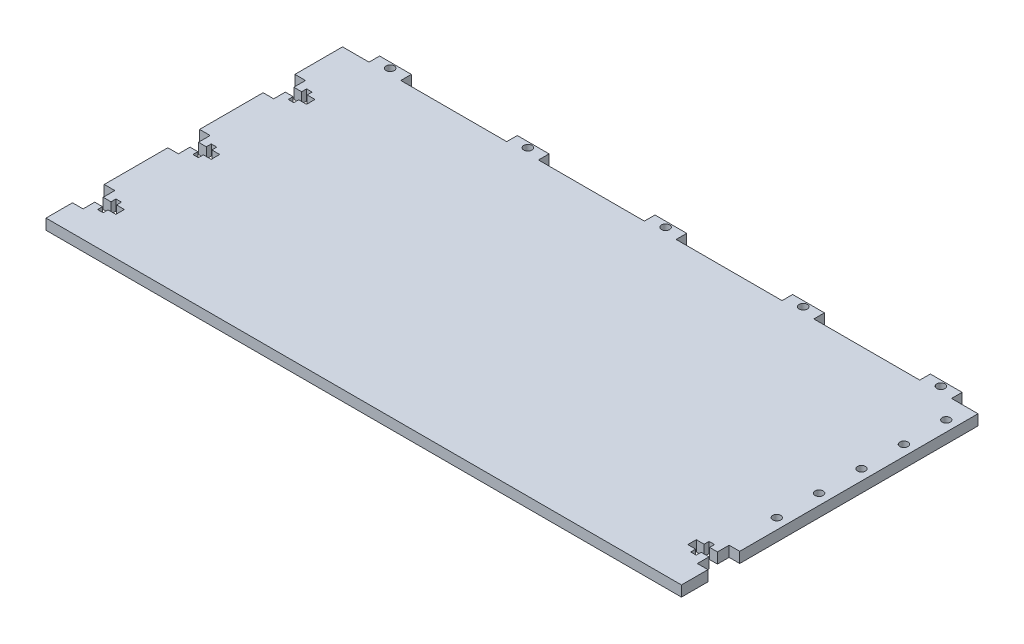
SolidWorks part; units mm, degrees
ref_plane "Front Plane" through (0, 0, 0) normal (0, 0, 1) x (1, 0, 0)
ref_plane "Top Plane" through (0, 0, 0) normal (0, 1, 0) x (1, 0, 0)
ref_plane "Right Plane" through (0, 0, 0) normal (1, 0, 0) x (0, 0, -1)
sketch "Sketch1" plane through (0, 0, 0) normal (0, 1, 0) x (1, 0, 0)
  line L1 (0, 0) -> (381, 0)
  line L2 (0, 0) -> (0, 177.8)
  line L3 (0, 177.8) -> (381, 177.8)
  line L4 (381, 0) -> (381, 177.8)
  dimension "D1" = 381
  dimension "D2" = 177.8
extrude "Boss-Extrude1" add sketch "Sketch1" along normal blind 6.35
sketch "Sketch2" plane through (0, 6.35, 0) normal (0, 1, 0) x (1, 0, 0)
  line L0 (381, 177.8) -> (0, 177.8) construction
  line L1 (15.875, 177.8) -> (34.925, 177.8)
  line L2 (15.875, 177.8) -> (15.875, 184.15)
  line L3 (15.875, 184.15) -> (34.925, 184.15)
  line L4 (34.925, 177.8) -> (34.925, 184.15)
  line L5 (0, 177.8) -> (0, 0) construction
  dimension "D1" = 19.05
  dimension "D2" = 6.35
  dimension "D3" = 15.875
extrude "Boss-Extrude2" add sketch "Sketch2" against normal blind 6.35
hole_wizard "#10 (0.1935) Diameter Hole1" positions "Sketch5" profile "Sketch4" hole size "#10" standard "ANSI Inch" end condition through all
sketch "Sketch5" plane through (0, 6.35, 0) normal (0, 1, 0) x (1, 0, 0)
  line L2 (15.875, 180.975) -> (34.925, 180.975) construction
  line L3 (15.875, 184.15) -> (15.875, 177.8) construction
  line L4 (34.925, 177.8) -> (34.925, 184.15) construction
  point P0 (25.4, 180.975)
sketch "Sketch4" plane through (25.4, 6.35, -180.975) normal (1, 0, 0) x (0, 0, 1)
  line L0 (0, 0) -> (0, 6.35)
  line L1 (0, 6.35) -> (2.4574, 6.35)
  line L2 (2.4574, 6.35) -> (2.4574, 0)
  line L5 (2.4574, 0) -> (0, 0)
  line L11 (0, -6.35) -> (0, 107.95) construction
  dimension "Thru Hole Dia." = 4.9149
  dimension "Thru Hole Depth" = 6.35
pattern_linear "LPattern1" count 5 spacing 82.55 along (1, 0, 0) of "#10 (0.1935) Diameter Hole1", "Boss-Extrude2"
sketch "Sketch7" plane through (0, 6.35, 0) normal (0, 1, 0) x (1, 0, 0)
  line L0 (0, 34.925) -> (0, 15.875)
  line L1 (0, 34.925) -> (6.35, 34.925)
  line L2 (6.35, 34.925) -> (6.35, 27.94)
  line L3 (0, 15.875) -> (6.35, 15.875)
  line L4 (6.35, 27.94) -> (11.049, 27.94)
  line L5 (19.05, 27.94) -> (19.05, 22.86)
  line L6 (6.35, 22.86) -> (11.049, 22.86)
  line L7 (14.351, 27.94) -> (19.05, 27.94)
  line L8 (14.351, 30.8991) -> (14.351, 27.94)
  line L9 (14.351, 30.8991) -> (11.049, 30.8991)
  line L10 (11.049, 30.8991) -> (11.049, 27.94)
  line L11 (14.351, 19.9009) -> (11.049, 19.9009)
  line L12 (14.351, 22.86) -> (14.351, 19.9009)
  line L13 (14.351, 22.86) -> (19.05, 22.86)
  line L14 (11.049, 22.86) -> (11.049, 19.9009)
  line L15 (6.35, 22.86) -> (6.35, 15.875)
  line L16 (0, 177.8) -> (0, 0) construction
  line L17 (15.875, 177.8) -> (0, 177.8) construction
  point P8 (19.05, 25.4)
  dimension "D1" = 6.35
  dimension "D2" = 5.08
  dimension "D3" = 12.7
  dimension "D4" = 10.9982
  dimension "D5" = 3.302
  dimension "D6" = 19.05
  dimension "D7" = 142.875
extrude "Cut-Extrude2" cut sketch "Sketch7" against normal through all
ref_plane "Plane2" through (190.5, 0, 0) normal (-1, 0, 0) x (0, 0, 1)
mirror "Mirror2" about plane through (190.5, 0, 0) normal (-1, 0, 0) of "Cut-Extrude2"
pattern_linear "LPattern4" count 3 spacing 57.15 along (0, 0, -1) of "Cut-Extrude2"
sketch "Sketch8" plane through (0, 6.35, 0) normal (0, 1, 0) x (1, 0, 0)
  line L0 (381, 177.8) -> (365.125, 177.8) construction
  line L1 (381, 34.925) -> (381, 177.8) construction
  line L2 (374.65, 177.8) -> (374.65, 0) construction
  line L3 (0, 0) -> (381, 0) construction
  circle A0 centre (374.65, 165.1) radius 2.413
  circle A1 centre (374.65, 139.7) radius 2.413
  circle A2 centre (374.65, 114.3) radius 2.413
  circle A3 centre (374.65, 88.9) radius 2.413
  circle A4 centre (374.65, 63.5) radius 2.413
  dimension "D1" = 4.826
  dimension "D2" = 12.7
  dimension "D3" = 6.35
  dimension "D5" = 25.4
  dimension "D4" = 5
extrude "Cut-Extrude3" cut sketch "Sketch8" against normal through all
